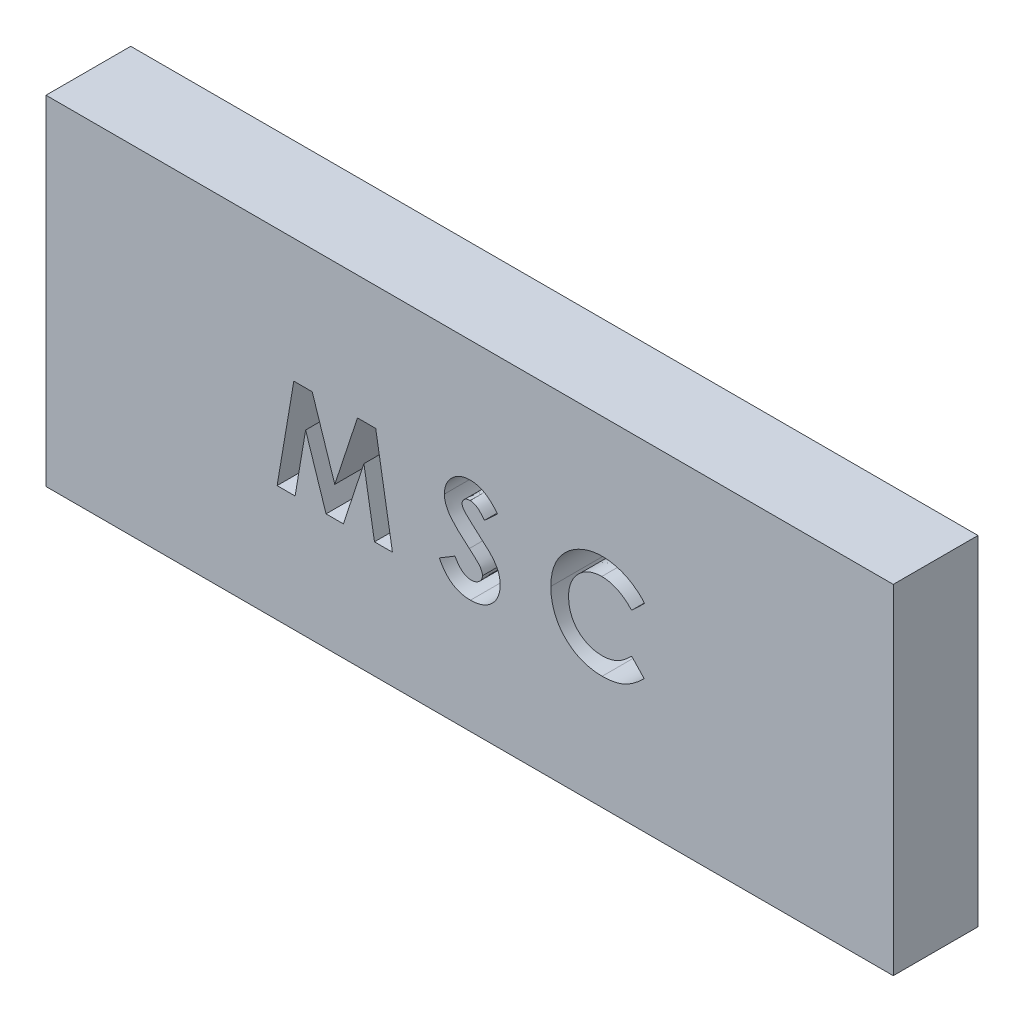
SolidWorks part; units mm, degrees
ref_plane "Plan de face" through (0, 0, 0) normal (0, 0, 1) x (1, 0, 0)
ref_plane "Plan de dessus" through (0, 0, 0) normal (0, 1, 0) x (1, 0, 0)
ref_plane "Plan de droite" through (0, 0, 0) normal (1, 0, 0) x (0, 0, -1)
sketch "Esquisse1" plane through (0, 0, 0) normal (0, 0, 1) x (1, 0, 0)
  line L1 (-15, 6) -> (15, 6)
  line L2 (-15, 6) -> (-15, -6)
  line L3 (-15, -6) -> (15, -6)
  line L4 (15, 6) -> (15, -6)
  text T0 "<b>M S C</b>"
  dimension "D1" = 30
  dimension "D2" = 12
  dimension "D3" = 6
  dimension "D4" = 15
extrude "Boss.-Extru.1" add sketch "Esquisse1" along normal blind 3
